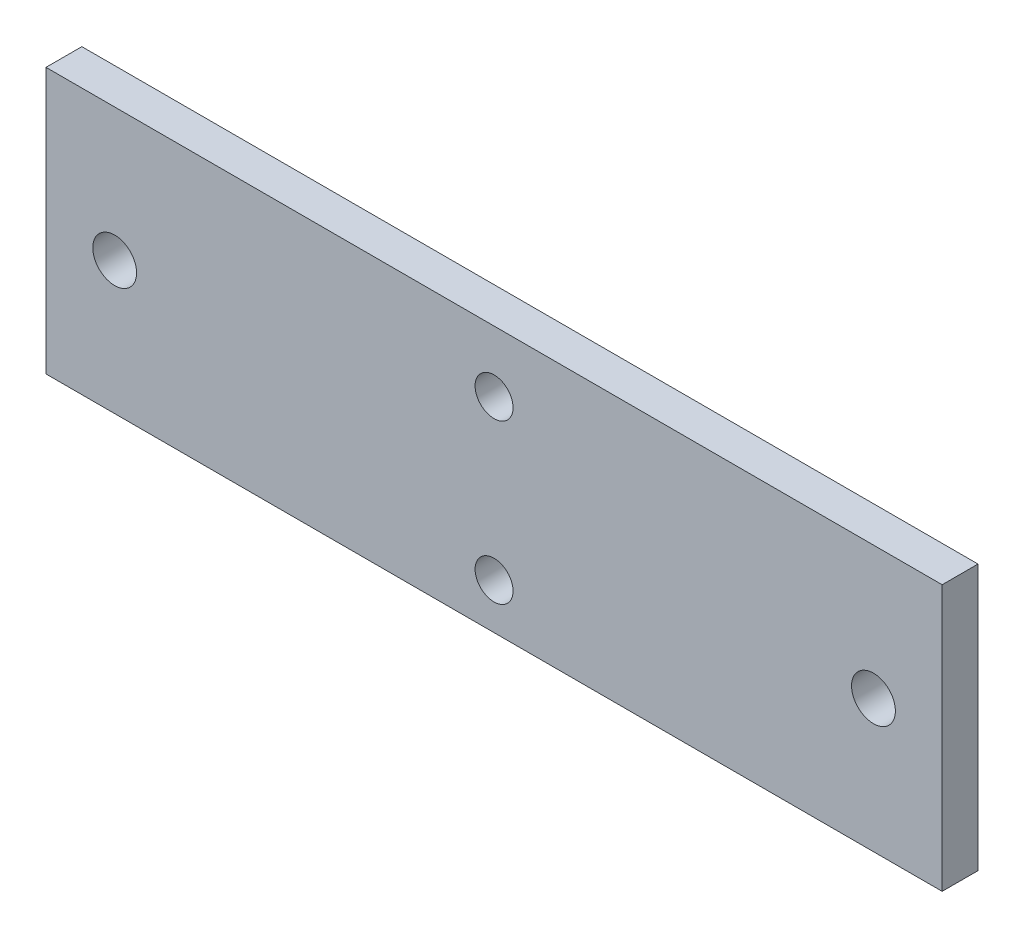
SolidWorks part; units mm, degrees
material "Acrylic (Medium-high impact)"
ref_plane "Front Plane" through (0, 0, 0) normal (0, 0, 1) x (1, 0, 0)
ref_plane "Top Plane" through (0, 0, 0) normal (0, 1, 0) x (1, 0, 0)
ref_plane "Right Plane" through (0, 0, 0) normal (1, 0, 0) x (0, 0, -1)
sketch "Sketch1" plane through (0, 0, 0) normal (0, 0, 1) x (1, 0, 0)
  line L1 (0, 0) -> (150, 0)
  line L2 (0, 0) -> (0, 44.45)
  line L3 (0, 44.45) -> (150, 44.45)
  line L4 (150, 0) -> (150, 44.45)
  dimension "D1" = 150
  dimension "D2" = 44.45
extrude "Boss-Extrude1" add sketch "Sketch1" along normal blind 6
sketch "Sketch2" plane through (0, 0, 6) normal (0, 0, 1) x (1, 0, 0)
  line L0 (0, 22.225) -> (150, 22.225) construction
  line L1 (0, 44.45) -> (0, 0) construction
  line L2 (150, 0) -> (150, 44.45) construction
  line L3 (75, 44.45) -> (75, 0) construction
  line L4 (150, 44.45) -> (0, 44.45) construction
  line L5 (0, 0) -> (150, 0) construction
  circle A1 centre (138.505, 22.225) radius 3.175 construction
  circle A2 centre (11.495, 22.225) radius 3.6662
  circle A3 centre (138.505, 22.225) radius 3.6662
  dimension "D2" = 63.505
extrude "Cut-Extrude1" cut sketch "Sketch2" against normal through all
sketch "Sketch3" plane through (0, 0, 0) normal (0, 0, -1) x (-1, 0, 0)
  line L0 (-75, 44.45) -> (-75, 0) construction
  line L1 (-150, 44.45) -> (0, 44.45) construction
  line L2 (0, 0) -> (-150, 0) construction
  circle A0 centre (-75, 7.62) radius 3.175
  circle A1 centre (-75, 34.198) radius 3.175
  dimension "D1" = 6.35
  dimension "D2" = 6.35
  dimension "D3" = 10.252
  dimension "D4" = 7.62
extrude "Cut-Extrude2" cut sketch "Sketch3" against normal through all
